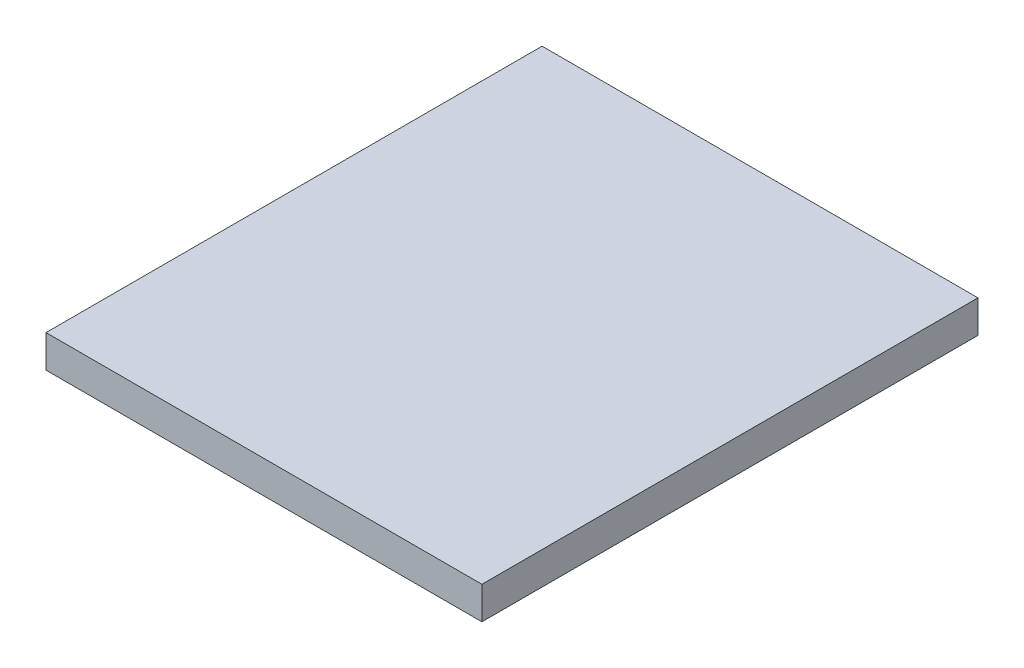
SolidWorks part; units mm, degrees
ref_plane "Front Plane" through (0, 0, 0) normal (0, 0, 1) x (1, 0, 0)
ref_plane "Top Plane" through (0, 0, 0) normal (0, 1, 0) x (1, 0, 0)
ref_plane "Right Plane" through (0, 0, 0) normal (1, 0, 0) x (0, 0, -1)
sketch "Sketch2" plane through (0, 0, 0) normal (0, 1, 0) x (1, 0, 0)
  line L1 (-17.018, -19.3675) -> (17.018, -19.3675)
  line L2 (-17.018, -19.3675) -> (-17.018, 19.3675)
  line L3 (-17.018, 19.3675) -> (17.018, 19.3675)
  line L4 (17.018, -19.3675) -> (17.018, 19.3675)
  line L5 (-17.018, -19.3675) -> (17.018, 19.3675) construction
  line L6 (-17.018, 19.3675) -> (17.018, -19.3675) construction
  point P0 (0, 0)
  dimension "D1" = 34.036
  dimension "D2" = 38.735
extrude "Boss-Extrude1" add sketch "Sketch2" along normal blind 2.54
